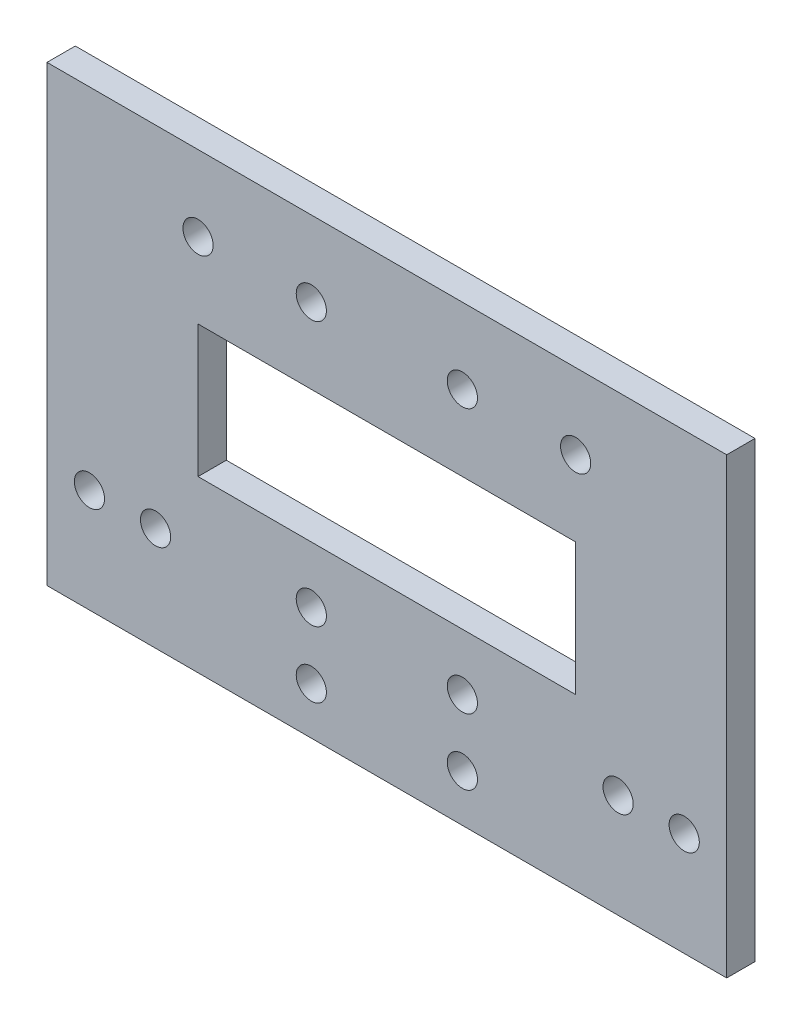
SolidWorks part; units mm, degrees
material "Thornel VCB-20 碳布"
ref_plane "前视基准面" through (0, 0, 0) normal (0, 0, 1) x (1, 0, 0)
ref_plane "上视基准面" through (0, 0, 0) normal (0, 1, 0) x (1, 0, 0)
ref_plane "右视基准面" through (0, 0, 0) normal (1, 0, 0) x (0, 0, -1)
other "Configuration Table"
sketch "草图1" plane through (0, 0, 0) normal (0, 0, 1) x (1, 0, 0)
  line L0 (0, 0) -> (0, 48)
  line L1 (0, 48) -> (72, 48)
  line L2 (72, 48) -> (72, 0)
  line L3 (72, 0) -> (56, 0)
  line L5 (56, 32) -> (16, 32)
  line L7 (16, 0) -> (0, 0)
  line L8 (16, 18) -> (56, 18)
  line L9 (16, 0) -> (56, 0)
  line L11 (16, 18) -> (16, 32)
  line L12 (56, 32) -> (56, 18)
  dimension "D1" = 16
  dimension "D2" = 16
  dimension "D3" = 40
  dimension "D4" = 16
  dimension "D5" = 48
  dimension "D6" = 18
  dimension "D7" = 16
  dimension "D8" = 16
extrude "凸台-拉伸2" add sketch "草图1" along normal blind 3
sketch "草图2" plane through (0, 0, 0) normal (0, 0, -1) x (-1, 0, 0)
  line L0 (-64, 12) -> (-8, 12) construction
  line L1 (-72, 0) -> (-72, 48) construction
  line L2 (0, 48) -> (0, 0) construction
  line L3 (0, 0) -> (-72, 0) construction
  line L4 (-44, 40) -> (-28, 40) construction
  line L5 (-72, 48) -> (0, 48) construction
  line L6 (1524, 48) -> (-76, 48) construction
  circle A0 centre (-64, 12) radius 1.6 construction
  circle A1 centre (-8, 12) radius 1.6 construction
  circle A2 centre (-44, 12) radius 1.6
  circle A3 centre (-28, 12) radius 1.6
  circle A4 centre (-44, 40) radius 1.6
  circle A5 centre (-28, 40) radius 1.6
  circle A6 centre (-56, 12) radius 1.6 construction
  circle A7 centre (-16, 12) radius 1.6 construction
  circle A8 centre (-56, 40) radius 1.6
  circle A9 centre (-16, 40) radius 1.6
  circle A10 centre (-44, 5) radius 1.6
  circle A11 centre (-28, 5) radius 1.6
  dimension "D1" = 3.2
  dimension "D7" = 3.2
  dimension "D2" = 8
  dimension "D3" = 8
  dimension "D4" = 20
  dimension "D5" = 20
  dimension "D6" = 12
  dimension "D8" = 16
  dimension "D9" = 8
  dimension "D10" = 28
  dimension "D11" = 12
  dimension "D12" = 12
  dimension "D13" = 12
  dimension "D14" = 12
  dimension "D15" = 8
  dimension "D16" = 8
  dimension "D17" = 7
  dimension "D18" = 7
  dimension "D19" = 28
  dimension "D20" = 28
extrude "切除-拉伸1" cut sketch "草图2" against normal blind 10
sketch "草图3" plane through (0, 0, 3) normal (0, 0, 1) x (1, 0, 0)
  line L0 (72, 0) -> (72, 48) construction
  line L1 (0, 0) -> (72, 0) construction
  line L2 (0, 48) -> (0, 0) construction
  circle A0 centre (67.5, 11) radius 1.6
  circle A1 centre (60.5, 11) radius 1.6
  circle A2 centre (4.5, 11) radius 1.6
  circle A3 centre (11.5, 11) radius 1.6
  dimension "D1" = 4.5
  dimension "D3" = 3.2
  dimension "D5" = 3.2
  dimension "D7" = 4.5
  dimension "D8" = 11.5
  dimension "D10" = 3.2
  dimension "D11" = 3.2
  dimension "D2" = 11
  dimension "D4" = 11.5
  dimension "D6" = 11
  dimension "D9" = 11
  dimension "D12" = 11
extrude "切除-拉伸2" cut sketch "草图3" against normal through all
